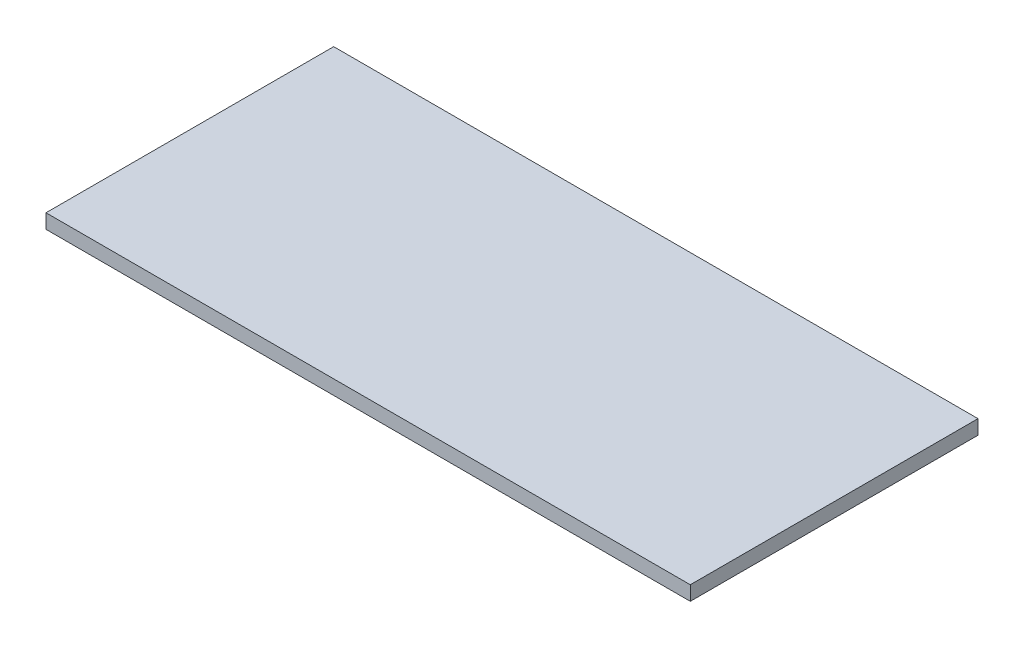
SolidWorks part; units mm, degrees
ref_plane "Front Plane" through (0, 0, 0) normal (0, 0, 1) x (1, 0, 0)
ref_plane "Top Plane" through (0, 0, 0) normal (0, 1, 0) x (1, 0, 0)
ref_plane "Right Plane" through (0, 0, 0) normal (1, 0, 0) x (0, 0, -1)
sketch "Sketch1" plane through (0, 0, 0) normal (0, 0, 1) x (1, 0, 0)
  line L0 (-53.1131, 0) -> (60.6504, 0)
extrude "Extrude-Thin1" add sketch "Sketch1" along normal blind 50.8 thin
